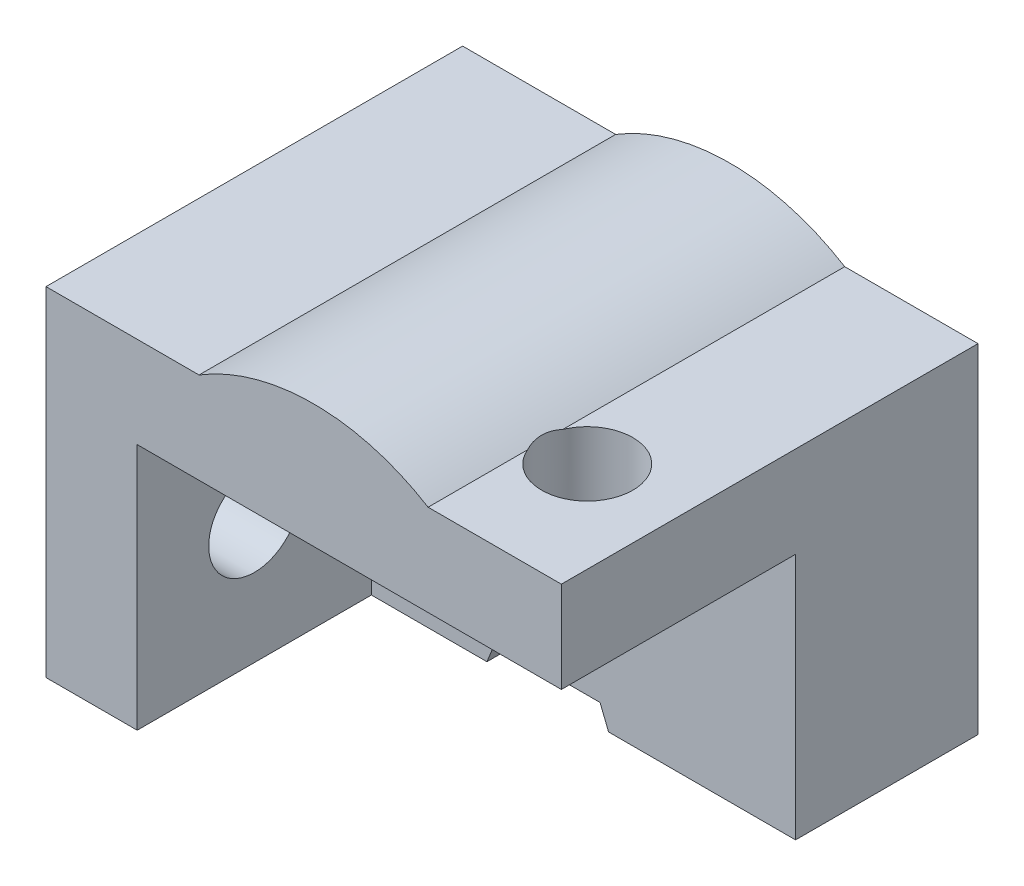
SolidWorks part; units mm, degrees
ref_plane "Спереди" through (0, 0, 0) normal (0, 0, 1) x (1, 0, 0)
ref_plane "Сверху" through (0, 0, 0) normal (0, 1, 0) x (1, 0, 0)
ref_plane "Справа" through (0, 0, 0) normal (1, 0, 0) x (0, 0, -1)
sketch "Эскиз1" plane through (0, 0, 0) normal (0, 0, 1) x (1, 0, 0)
  line L3 (-416.1175, 132.3377) -> (-409.3175, 132.3377)
  line L4 (-399.1675, 143.4738) -> (-399.1675, 132.3377)
  line L12 (-399.1675, 143.5738) -> (-399.1675, 147.5738) construction
  line L15 (-403.5508, 143.4738) -> (-399.1675, 143.4738)
  line L16 (-416.1175, 143.4738) -> (-411.0842, 143.4738)
  line L18 (-416.1175, 132.3377) -> (-416.1175, 143.4738)
  line L19 (-409.3175, 132.3377) -> (-409.0375, 133.0377)
  line L21 (-405.5975, 133.0377) -> (-405.3175, 132.3377)
  line L22 (-409.0375, 133.0377) -> (-405.5975, 133.0377)
  line L23 (-405.3175, 132.3377) -> (-399.1675, 132.3377)
  circle A4 centre (-407.3175, 137.3377) radius 5 construction
  arc A6 (-403.5508, 143.4738) -> (-411.0842, 143.4738) centre (-407.3175, 137.3377) ccw
  dimension "D5" = 0.7
extrude "Бобышка-Вытянуть1" add sketch "Эскиз1" against normal blind 6
ref_point "Точка1"
ref_plane "Плоскость4" through (-407.3175, 0, 0) normal (1, 0, 0) x (0, 0, -1)
sketch "Эскиз2" plane through (-407.3175, 0, 0) normal (1, 0, 0) x (0, 0, -1)
  line L0 (5.85, 142.3377) -> (2.15, 142.3377)
  line L1 (2.15, 132.3377) -> (5.85, 132.3377)
  line L3 (5.85, 142.3377) -> (2, 142.3377) construction
  line L5 (2.1, 138.8377) -> (6.1, 138.8377) construction
  line L6 (6.1, 135.8377) -> (2.1, 135.8377) construction
  line L7 (4.1, 135.8377) -> (4.1, 138.8377) construction
  line L8 (4.1, 137.3377) -> (2.3072, 137.3377) construction
  line L9 (2, 142.1877) -> (2, 141.3377)
  line L10 (2, 133.3377) -> (2, 132.4877)
  line L11 (6.1351, 142.4377) -> (1.9, 142.4377)
  line L12 (2, 142.3377) -> (2, 141.3377) construction
  line L13 (1.9, 142.4377) -> (1.9, 141.1092)
  line L14 (5.85, 142.4377) -> (1.9, 142.4377) construction
  line L15 (1.9, 142.4377) -> (1.9, 141.3377) construction
  line L16 (1.9, 141.1092) -> (1.4, 141.1092)
  line L17 (1.4, 141.1092) -> (1.4, 137.3377)
  line L18 (1.4, 137.3377) -> (6.1351, 137.3377)
  line L19 (6.1351, 137.3377) -> (6.1351, 142.4377)
  point P11 (4.1, 137.3377)
  dimension "D1" = 0.1
revolve "Вырез-Повернуть1" cut sketch "Эскиз2" angle 360 about L8
sketch "Эскиз3" plane through (0, 0, 0) normal (0, 0, 1) x (1, 0, 0)
  line L9 (-416.1175, 132.3377) -> (-409.3175, 132.3377) construction
  line L18 (-413.1175, 140.4738) -> (-413.1175, 135.3377)
  line L19 (-413.1175, 135.3377) -> (-411.3486, 135.3377)
  line L20 (-411.3486, 135.3377) -> (-411.0686, 136.0377)
  line L21 (-411.0686, 136.0377) -> (-403.5664, 136.0377)
  line L22 (-403.5664, 136.0377) -> (-403.2864, 135.3377)
  line L23 (-403.2864, 135.3377) -> (-402.1675, 135.3377)
  line L24 (-402.1675, 135.3377) -> (-402.1675, 140.4738)
  line L25 (-402.1675, 140.4738) -> (-404.5238, 140.4738)
  line L26 (-410.1112, 140.4738) -> (-413.1175, 140.4738)
  line L27 (-413.1175, 140.4738) -> (-413.1175, 132.3377)
  line L35 (-399.1675, 140.4738) -> (-413.1175, 140.4738)
  line L36 (-416.1175, 143.4738) -> (-416.1175, 132.3377)
  line L37 (-416.1175, 132.3377) -> (-409.3175, 132.3377)
  line L38 (-409.3175, 132.3377) -> (-409.0375, 133.0377)
  line L39 (-409.0375, 133.0377) -> (-405.5975, 133.0377)
  line L40 (-405.5975, 133.0377) -> (-405.3175, 132.3377)
  line L41 (-405.3175, 132.3377) -> (-399.1675, 132.3377)
  line L42 (-399.1675, 132.3377) -> (-399.1675, 143.4738)
  line L43 (-399.1675, 143.4738) -> (-403.5508, 143.4738)
  line L44 (-411.0842, 143.4738) -> (-416.1175, 143.4738)
  line L45 (-416.1175, 143.4738) -> (-416.1175, 132.3377)
  line L46 (-416.1175, 132.3377) -> (-413.1175, 132.3377)
  line L51 (-399.1675, 140.4738) -> (-399.1675, 143.4738)
  line L52 (-399.1675, 143.4738) -> (-403.5508, 143.4738)
  line L53 (-411.0842, 143.4738) -> (-416.1175, 143.4738)
  arc A2 (-404.5238, 140.4738) -> (-410.1112, 140.4738) centre (-407.3175, 137.3377) ccw
  arc A4 (-403.5508, 143.4738) -> (-411.0842, 143.4738) centre (-407.3175, 137.3377) ccw
  arc A5 (-403.5508, 143.4738) -> (-411.0842, 143.4738) centre (-407.3175, 137.3377) ccw
  dimension "D1" = 3
  dimension "D2" = 0
extrude "Бобышка-Вытянуть2" add sketch "Эскиз3" along normal up to surface (7.7022 mm away)
sketch "Эскиз4" plane through (-413.1175, 0, 0) normal (1, 0, 0) x (0, 0, -1)
  circle A0 centre (-3.8511, 136.4058) radius 1.5
extrude "Вырез-Вытянуть1" cut sketch "Эскиз4" against normal blind 6
sketch "Эскиз5" plane through (0, 140.4738, 0) normal (0, -1, 0) x (1, 0, 0)
  line L0 (-399.1675, 7.7022) -> (-399.1675, 0) construction
  circle A0 centre (-402.1675, 3.8511) radius 1.5
  dimension "D1" = 3
extrude "Вырез-Вытянуть2" cut sketch "Эскиз5" against normal blind 6
